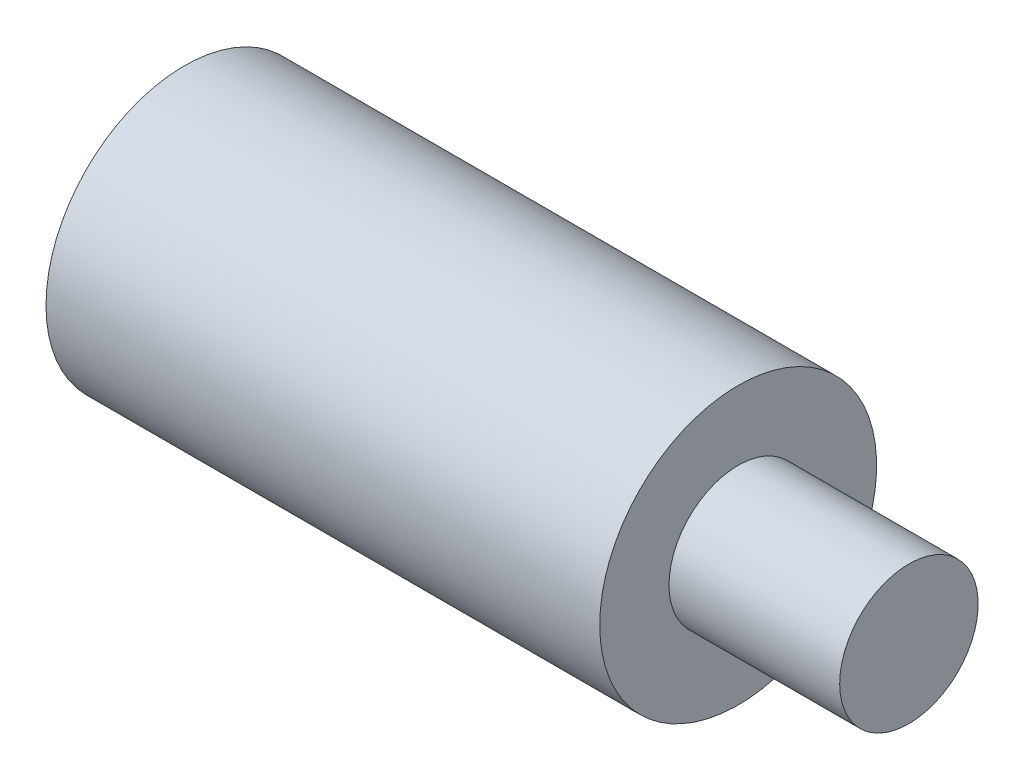
SolidWorks part; units mm, degrees
ref_plane "Спереди" through (0, 0, 0) normal (0, 0, 1) x (1, 0, 0)
ref_plane "Сверху" through (0, 0, 0) normal (0, 1, 0) x (1, 0, 0)
ref_plane "Справа" through (0, 0, 0) normal (1, 0, 0) x (0, 0, -1)
sketch "Эскиз1" plane through (0, 0, 0) normal (0, 0, 1) x (1, 0, 0)
  line L0 (-97.0894, 0) -> (88.796, 0) construction
  line L1 (7.2, -1.5) -> (7.2, 0)
  line L2 (3.5, -1.5) -> (7.2, -1.5)
  line L3 (3.5, -1.5) -> (3.5, -3)
  line L4 (3.5, -3) -> (-8.5, -3)
  line L5 (-8.5, -3) -> (-8.5, -1.2)
  line L6 (-8.5, -1.2) -> (-0.5, -1.2)
  line L7 (-0.5, -1.2) -> (0.3, 0)
  line L8 (7.2, 0) -> (0.3, 0)
  dimension "D2" = 1.2
  dimension "D3" = 8
  dimension "D4" = 0.8
  dimension "D5" = 3
  dimension "D6" = 12
  dimension "D7" = 3.7
revolve "Основание-Повернуть" add sketch "Эскиз1" angle 360 about L0
cosmetic thread "Условное изображение резьбы1" parameters "D1"=6, "D2"=3
cosmetic thread "Условное изображение резьбы2" parameters "D1"=6, "D2"=2.5
cosmetic thread "Условное изображение резьбы3" parameters "D1"=6, "D2"=3
cosmetic thread "Условное изображение резьбы4" parameters "D1"=6, "D2"=3
cosmetic thread "Условное изображение резьбы5" parameters "D1"=6, "D2"=3
cosmetic thread "Условное изображение резьбы6" parameters "D1"=6, "D2"=3
cosmetic thread "Условное изображение резьбы7" parameters "D1"=6, "D2"=3
cosmetic thread "Условное изображение резьбы8" parameters "D1"=6, "D2"=3
cosmetic thread "Условное изображение резьбы9" parameters "D1"=6, "D2"=3
cosmetic thread "Условное изображение резьбы10" parameters "D1"=6, "D2"=3
cosmetic thread "Условное изображение резьбы11"
chamfer "Фаска1" distance 0.4 angle 45 1 edges at (-8.5, 0, 1.2)
